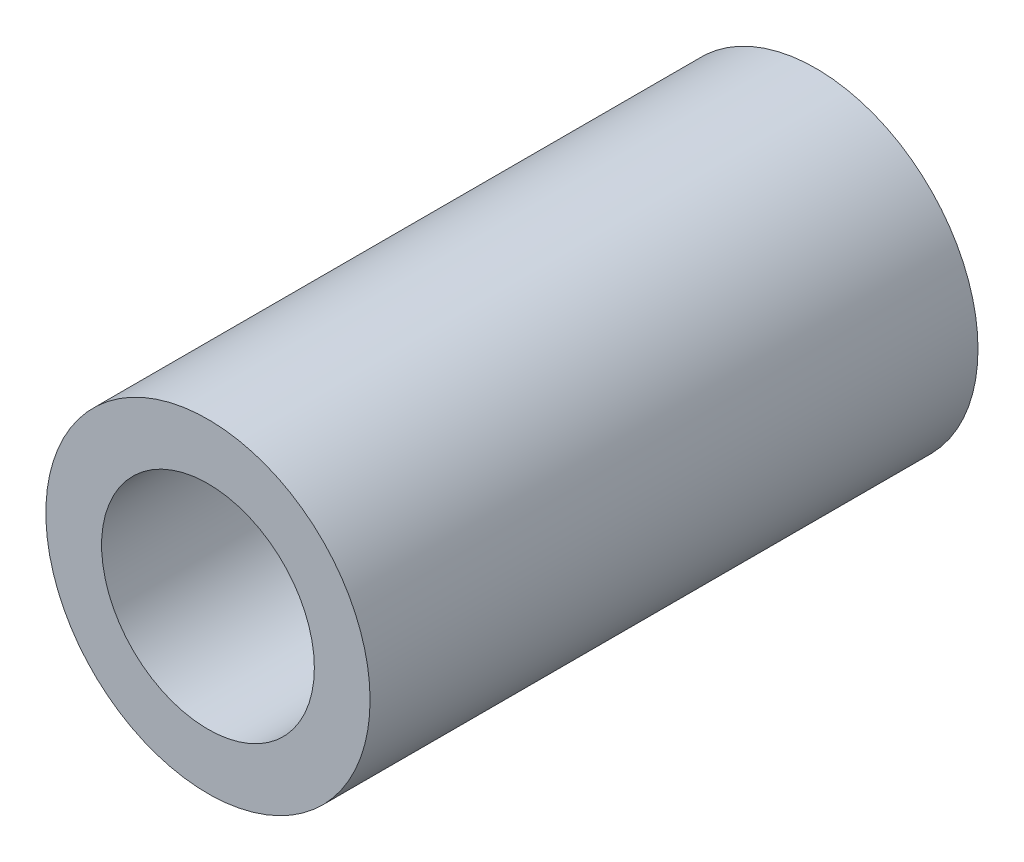
SolidWorks part; units mm, degrees
material "Plain Carbon Steel"
ref_plane "Front Plane" through (0, 0, 0) normal (0, 0, 1) x (1, 0, 0)
ref_plane "Top Plane" through (0, 0, 0) normal (0, 1, 0) x (1, 0, 0)
ref_plane "Right Plane" through (0, 0, 0) normal (1, 0, 0) x (0, 0, -1)
sketch "Sketch1" plane through (0, 0, 0) normal (0, 0, 1) x (1, 0, 0)
  circle A0 centre (0, 0) radius 5.25
  circle A1 centre (0, 0) radius 8
  dimension "D1" = 10.5
  dimension "D2" = 16
extrude "Boss-Extrude1" add sketch "Sketch1" along normal mid plane 30
